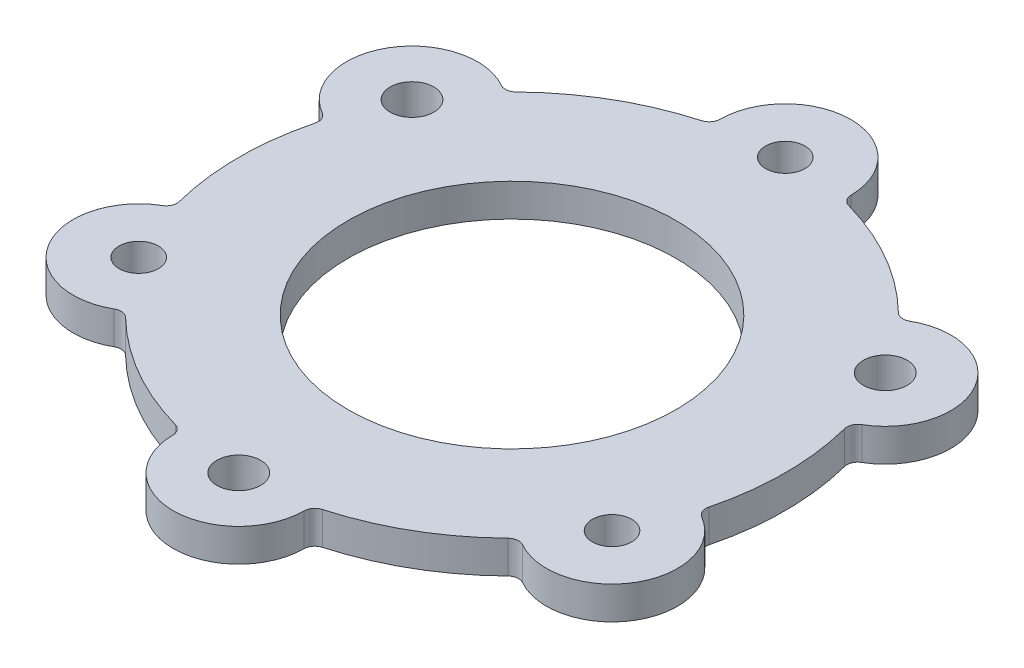
SolidWorks part; units mm, degrees
material "Delrin 2700 NC010, Low Viscosity Acetal Copolymer (SS)"
ref_plane "Front" through (0, 0, 0) normal (0, 0, 1) x (1, 0, 0)
ref_plane "Top" through (0, 0, 0) normal (0, 1, 0) x (1, 0, 0)
ref_plane "Right" through (0, 0, 0) normal (1, 0, 0) x (0, 0, -1)
sketch "Sketch1" plane through (0, 0, 0) normal (0, 1, 0) x (1, 0, 0)
  line L0 (0, 0) -> (-10.8253, -6.25) construction
  line L5 (0, 0) -> (0, -12.5) construction
  line L8 (3, 0) -> (3, -12.5)
  line L9 (-3, 0) -> (-3, -12.5)
  line L10 (1.5, -2.5981) -> (-9.3253, -8.8481)
  line L11 (-1.5, 2.5981) -> (-12.3253, -3.6519)
  line L12 (0, 0) -> (-10.8253, 6.25) construction
  line L13 (-1.5, -2.5981) -> (-12.3253, 3.6519)
  line L14 (1.5, 2.5981) -> (-9.3253, 8.8481)
  line L15 (0, 0) -> (0, 12.5) construction
  line L16 (-3, 0) -> (-3, 12.5)
  line L17 (3, 0) -> (3, 12.5)
  line L18 (0, 0) -> (10.8253, 6.25) construction
  line L19 (-1.5, 2.5981) -> (9.3253, 8.8481)
  line L20 (1.5, -2.5981) -> (12.3253, 3.6519)
  line L21 (0, 0) -> (10.8253, -6.25) construction
  line L22 (1.5, 2.5981) -> (12.3253, -3.6519)
  line L23 (-1.5, -2.5981) -> (9.3253, -8.8481)
  circle A1 centre (0, 0) radius 7.5
  arc A11 (3, 0) -> (-3, 0) centre (0, 0) ccw
  arc A12 (-3, -12.5) -> (3, -12.5) centre (0, -12.5) ccw
  circle A13 centre (0, -12.5) radius 1
  arc A15 (1.5, -2.5981) -> (-1.5, 2.5981) centre (0, 0) ccw
  arc A16 (-12.3253, -3.6519) -> (-9.3253, -8.8481) centre (-10.8253, -6.25) ccw
  circle A17 centre (-10.8253, 6.25) radius 1
  arc A18 (-1.5, -2.5981) -> (1.5, 2.5981) centre (0, 0) ccw
  arc A19 (-9.3253, 8.8481) -> (-12.3253, 3.6519) centre (-10.8253, 6.25) ccw
  circle A21 centre (0, 0) radius 12.5
  arc A23 (-3, 0) -> (3, 0) centre (0, 0) ccw
  arc A24 (3, 12.5) -> (-3, 12.5) centre (0, 12.5) ccw
  circle A25 centre (10.8253, 6.25) radius 1
  arc A26 (-1.5, 2.5981) -> (1.5, -2.5981) centre (0, 0) ccw
  arc A27 (12.3253, 3.6519) -> (9.3253, 8.8481) centre (10.8253, 6.25) ccw
  arc A29 (1.5, 2.5981) -> (-1.5, -2.5981) centre (0, 0) ccw
  arc A30 (9.3253, -8.8481) -> (12.3253, -3.6519) centre (10.8253, -6.25) ccw
  circle A31 centre (-10.8253, -6.25) radius 1 [skipped]
  circle A32 centre (10.8253, -6.25) radius 1 [skipped]
  circle A33 centre (0, 12.5) radius 1 [skipped]
  circle A34 centre (0, 12.5) radius 0.9
  circle A35 centre (10.8253, -6.25) radius 0.9
  circle A36 centre (-10.8253, -6.25) radius 0.9
  point P6 (-5.4127, -3.125)
  point P10 (0, -6.25)
  point P22 (-5.4127, 3.125)
  point P30 (0, -15.5)
  point P32 (0, 6.25)
  point P40 (5.4127, 3.125)
  point P48 (5.4127, -3.125)
  dimension "D1" = 1.8
  dimension "D2" = 15
  dimension "D3" = 6
  dimension "D5" = 25
  dimension "D6" = 3
  dimension "D7" = 2
  dimension "D4" = 3
  dimension "D8" = 12.5
extrude "Boss-Extrude1" add sketch "Sketch1" along normal blind 1.5
fillet "Fillet1" radius 0.5 12 edges at (-3, 0.75, 12.1347) (3, 0.75, 12.1347) (9.0089, 0.75, 8.6654) (12.0089, 0.75, 3.4693) (12.0089, 0.75, -3.4693) (9.0089, 0.75, -8.6654) (3, 0.75, -12.1347) (-3, 0.75, -12.1347) (-9.0089, 0.75, -8.6654) (-12.0089, 0.75, -3.4693) (-12.0089, 0.75, 3.4693) (-9.0089, 0.75, 8.6654)
